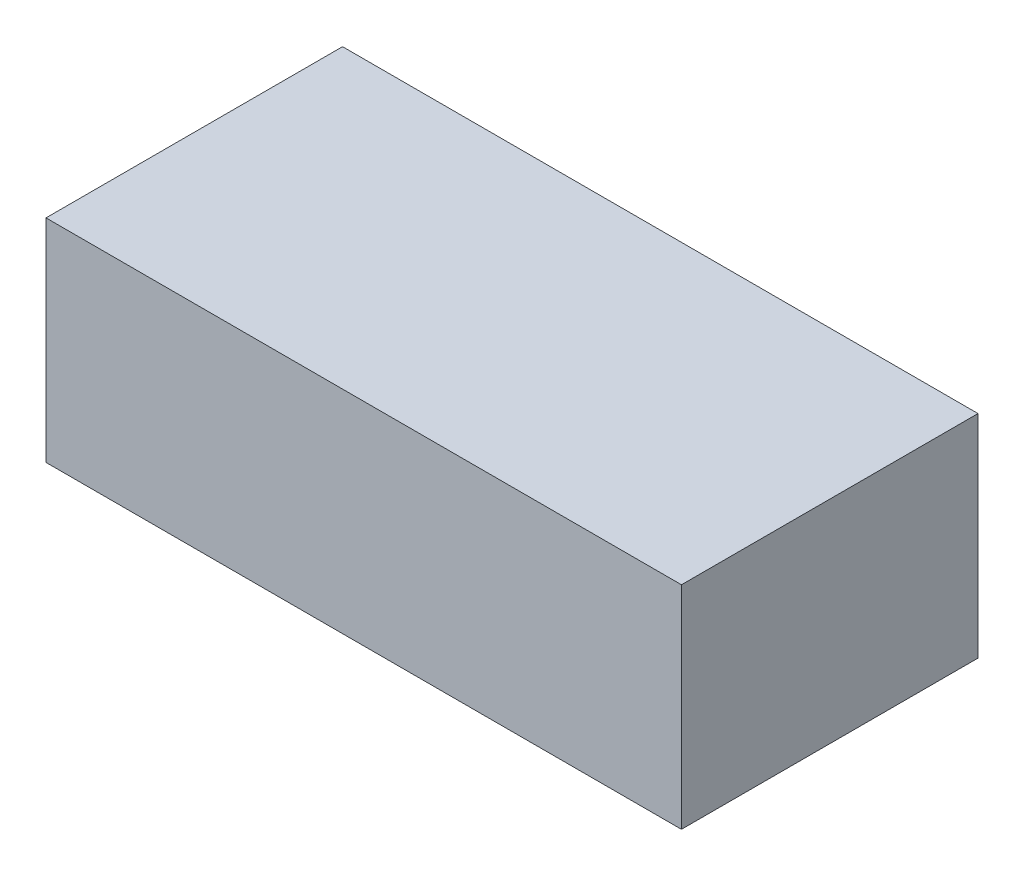
SolidWorks part; units mm, degrees
ref_plane "Alzado" through (0, 0, 0) normal (0, 0, 1) x (1, 0, 0)
ref_plane "Planta" through (0, 0, 0) normal (0, 1, 0) x (1, 0, 0)
ref_plane "Vista lateral" through (0, 0, 0) normal (1, 0, 0) x (0, 0, -1)
sketch "Croquis2" plane through (0, 0, 0) normal (0, 0, 1) x (1, 0, 0)
  line L1 (0, 0) -> (75, 0)
  line L2 (0, 0) -> (0, 25)
  line L3 (0, 25) -> (75, 25)
  line L4 (75, 0) -> (75, 25)
  dimension "D1" = 75
  dimension "D2" = 25
extrude "Saliente-Extruir1" add sketch "Croquis2" along normal blind 35
